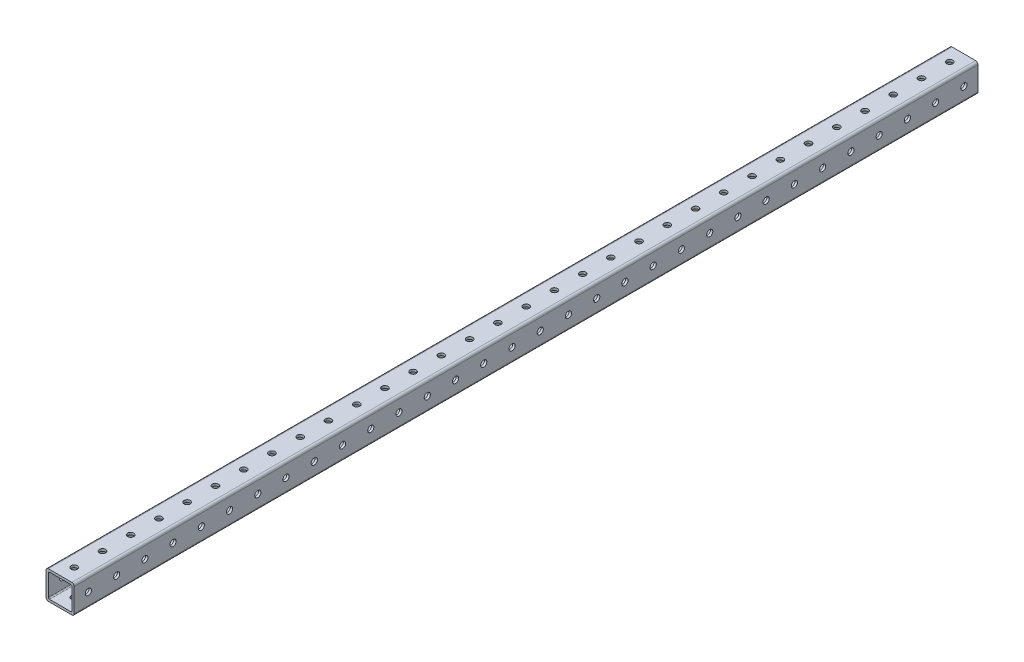
SolidWorks part; units mm, degrees
material "6063-T4"
ref_plane "Front Plane" through (0, 0, 0) normal (0, 0, 1) x (1, 0, 0)
ref_plane "Top Plane" through (0, 0, 0) normal (0, 1, 0) x (1, 0, 0)
ref_plane "Right Plane" through (0, 0, 0) normal (1, 0, 0) x (0, 0, -1)
sketch "Sketch1" plane through (0, 0, 0) normal (0, 0, 1) x (1, 0, 0)
  line L0 (-19.05, -19.05) -> (19.05, 19.05) construction
  line L1 (-15.875, 19.05) -> (15.875, 19.05)
  line L2 (-19.05, 15.875) -> (-19.05, -15.875)
  line L3 (-15.875, -19.05) -> (15.875, -19.05)
  line L4 (19.05, 15.875) -> (19.05, -15.875)
  arc A0 (15.875, 19.05) -> (19.05, 15.875) centre (15.875, 15.875) cw
  arc A1 (15.875, -19.05) -> (19.05, -15.875) centre (15.875, -15.875) ccw
  arc A2 (-19.05, -15.875) -> (-15.875, -19.05) centre (-15.875, -15.875) ccw
  arc A3 (-15.875, 19.05) -> (-19.05, 15.875) centre (-15.875, 15.875) ccw
  dimension "D1" = 3.175
  dimension "D2" = 38.1
extrude "Extrude-Thin1" add sketch "Sketch1" along normal mid plane 1219.2 thin
fillet "Fillet1" radius 1.6002 4 edges at (15.875, -15.875, 0) (15.875, 15.875, 0) (-15.875, 15.875, 0) (-15.875, -15.875, 0)
sketch "Sketch2" plane through (0, 0, 0) normal (0, 1, 0) x (1, 0, 0)
  line L0 (14.2748, -609.6) -> (-14.2748, -609.6) construction
  line L1 (0, -590.55) -> (0, -552.45) construction
  circle A0 centre (0, -590.55) radius 4.1656
  point P2 (0, -609.6)
  dimension "Bolt Hole" = 8.3312
  dimension "1/2 of Center to Center" = 19.05
  dimension "Center to Center" = 38.1
extrude "Cut-Extrude1" cut sketch "Sketch2" against normal through all and the other way through all
ref_axis "Axis1" through (0, 0, 590.55) along (0, 0, -1)
pattern_linear "LPattern1" count 32 spacing 38.1 along (0, 0, -1) of "Cut-Extrude1"
pattern_circular "CirPattern1" count 2 over 90 about axis through (0, 0, 590.55) along (0, 0, -1) of "LPattern1", "Cut-Extrude1"
equation "\"1/2 of Center to Center@Sketch2\" = \"Center to Center@Sketch2\"/2"
equation "\"D1@LPattern1\" = \"Length@Extrude-Thin1\"/\"Center to Center@Sketch2\""
equation "\"D3@LPattern1\" = \"Center to Center@Sketch2\""
